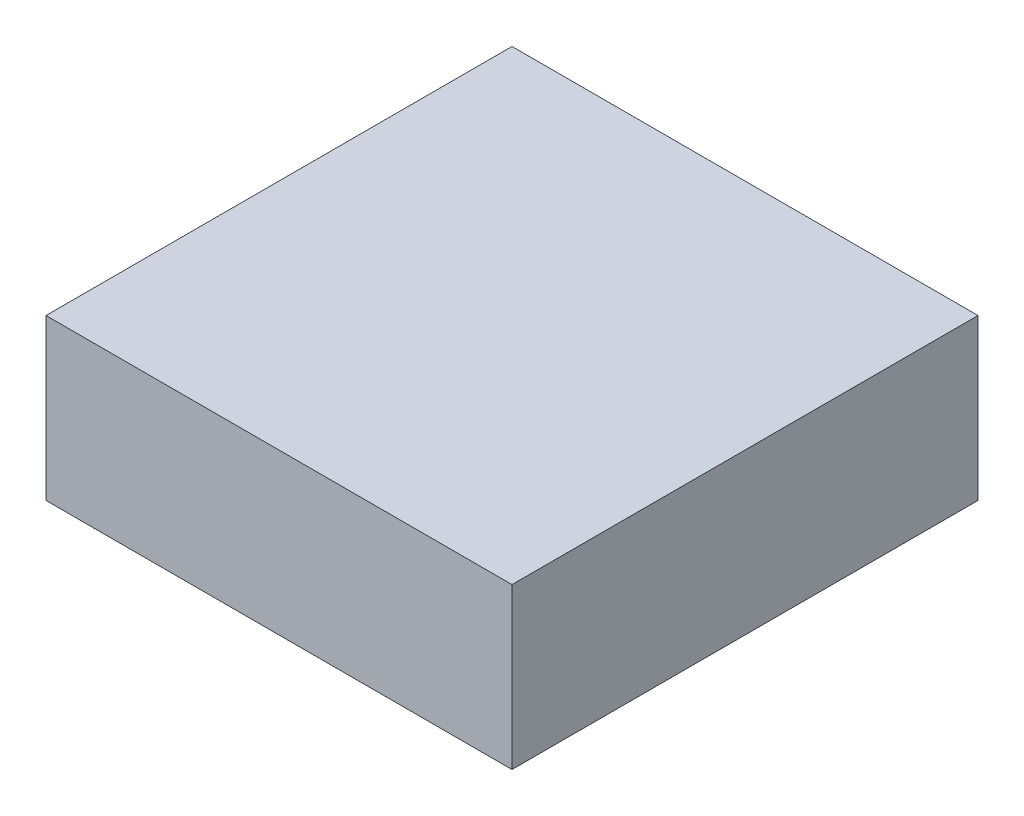
SolidWorks part; units mm, degrees
ref_plane "Front Plane" through (0, 0, 0) normal (0, 0, 1) x (1, 0, 0)
ref_plane "Top Plane" through (0, 0, 0) normal (0, 1, 0) x (1, 0, 0)
ref_plane "Right Plane" through (0, 0, 0) normal (1, 0, 0) x (0, 0, -1)
sketch "Sketch1" plane through (0, 0, 0) normal (0, 1, 0) x (1, 0, 0)
  line L1 (-32, 32) -> (32, 32)
  line L2 (-32, 32) -> (-32, -32)
  line L3 (-32, -32) -> (32, -32)
  line L4 (32, 32) -> (32, -32)
  line L5 (-32, 32) -> (32, -32) construction
  line L6 (-32, -32) -> (32, 32) construction
  point P0 (0, 0)
  dimension "D1" = 64
  dimension "D2" = 64
extrude "Boss-Extrude1" add sketch "Sketch1" along normal blind 22
